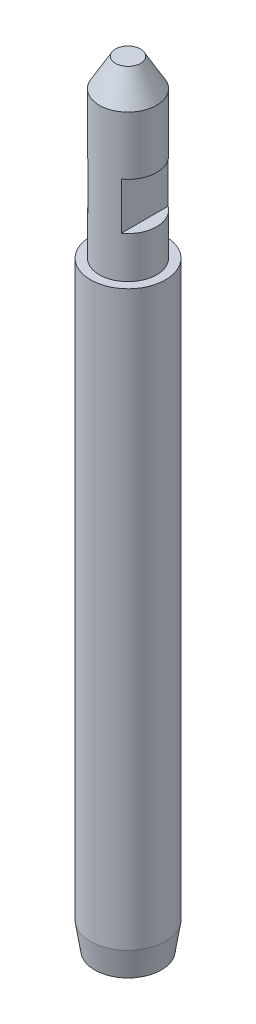
SolidWorks part; units mm, degrees
ref_plane "Face" through (0, 0, 0) normal (0, 0, 1) x (1, 0, 0)
ref_plane "Dessus" through (0, 0, 0) normal (0, 1, 0) x (1, 0, 0)
ref_plane "Droite" through (0, 0, 0) normal (1, 0, 0) x (0, 0, -1)
sketch "Esquisse2" plane through (0, 0, 0) normal (0, 0, 1) x (1, 0, 0)
  line L1 (-100.191, 30) -> (-100.191, 125.6202) construction
  line L2 (-100.191, 30) -> (-104.1962, 30)
  line L3 (-100.191, 123) -> (-100.191, 30)
  line L4 (-104.691, 33.2188) -> (-104.691, 102)
  line L5 (-103.641, 119.6225) -> (-103.641, 102)
  line L8 (-104, 102) -> (-98, 102) construction
  line L9 (-103.641, 102) -> (-104.691, 102)
  line L10 (-101.691, 123) -> (-100.191, 123)
  line L11 (-98.75, 30) -> (-103.25, 30) construction
  line L12 (-104.691, 33.2188) -> (-104.1962, 30)
  line L13 (-101.691, 123) -> (-103.641, 119.6225)
  dimension "D1" = 21
  dimension "D2" = 4.5
  dimension "D3" = 3.45
  dimension "D6" = 60
revolve "Révolution1" add sketch "Esquisse2" angle 360 about L1
sketch "Esquisse4" plane through (0, 30, 0) normal (0, -1, 0) x (1, 0, 0)
  circle A0 centre (-100.191, 0) radius 1.6
extrude "Enlèv. mat.-Extru.1" cut sketch "Esquisse4" against normal blind 10
ref_plane "Plan1" through (0, 29.5, 0) normal (0, 1, 0) x (-1, 0, 0)
sketch "Esquisse5" plane through (0, 29.5, 0) normal (0, 1, 0) x (-1, 0, 0)
  line L0 (102.891, -3.5231) -> (102.891, 3.7543)
  line L1 (100.191, -2.6753) -> (100.191, 6.2743) construction
  line L2 (102.891, -3.5231) -> (105.7586, 0)
  line L3 (105.7586, 0) -> (102.891, 3.7543)
  dimension "D1" = 2.7
extrude "Enlèv. mat.-Extru.2" [suppressed] cut sketch "Esquisse5" along normal blind 11
sketch "Esquisse6" plane through (0, 0, 0) normal (0, 0, 1) x (1, 0, 0)
  line L0 (-100.191, 120.2811) -> (-100.191, 104.3002) construction
  line L1 (-105.0845, 112.6358) -> (-102.191, 112.6358)
  line L2 (-105.0845, 112.6358) -> (-105.0845, 107)
  line L3 (-105.0845, 107) -> (-102.191, 107)
  line L4 (-102.191, 112.6358) -> (-102.191, 107)
  line L5 (-100.191, 102) -> (-100.191, 119.6225) construction
  line L6 (-95.2976, 107) -> (-98.191, 107)
  line L7 (-95.2976, 112.6358) -> (-95.2976, 107)
  line L8 (-95.2976, 112.6358) -> (-98.191, 112.6358)
  line L9 (-98.191, 112.6358) -> (-98.191, 107)
  line L10 (-95.691, 102) -> (-104.691, 102) construction
  dimension "D1" = 2
  dimension "D2" = 5
extrude "Enlèv. mat.-Extru.3" cut sketch "Esquisse6" against normal mid plane 11
